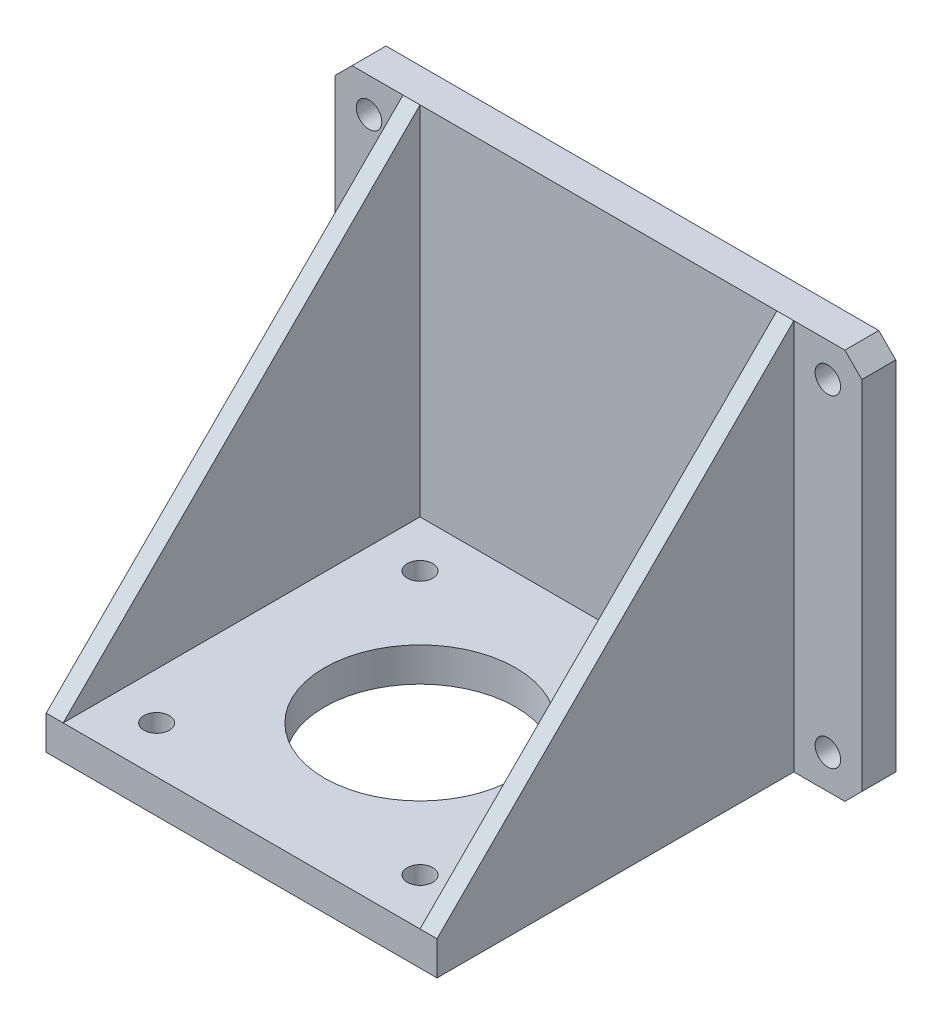
SolidWorks part; units mm, degrees
ref_plane "Front" through (0, 0, 0) normal (0, 0, 1) x (1, 0, 0)
ref_plane "Top" through (0, 0, 0) normal (0, 1, 0) x (1, 0, 0)
ref_plane "Right" through (0, 0, 0) normal (1, 0, 0) x (0, 0, -1)
sketch "Sketch1" plane through (0, 0, 0) normal (0, 1, 0) x (1, 0, 0)
  line L1 (0, 0) -> (46, 0)
  line L2 (0, 0) -> (0, 46)
  line L3 (0, 46) -> (46, 46)
  line L4 (46, 0) -> (46, 46)
  dimension "D1" = 46
  dimension "D2" = 46
extrude "Boss-Extrude1" add sketch "Sketch1" along normal blind 4
sketch "Sketch2" plane through (0, 4, 0) normal (0, 1, 0) x (1, 0, 0)
  line L0 (46, 0) -> (46, 46) construction
  line L1 (0, 46) -> (46, 46)
  line L2 (0, 46) -> (0, 42)
  line L3 (0, 42) -> (46, 42)
  line L4 (46, 46) -> (46, 42)
  dimension "D1" = 4
extrude "Boss-Extrude2" add sketch "Sketch2" along normal blind 42
sketch "Sketch3" plane through (0, 4, 0) normal (0, 1, 0) x (1, 0, 0)
  line L0 (0, 42) -> (46, 42) construction
  line L1 (0, 0) -> (2, 0)
  line L2 (0, 0) -> (0, 42)
  line L3 (0, 42) -> (2, 42)
  line L4 (2, 0) -> (2, 42)
  line L6 (44, 42) -> (46, 42)
  line L7 (44, 42) -> (44, 0)
  line L8 (44, 0) -> (46, 0)
  line L9 (46, 42) -> (46, 0)
  dimension "D1" = 2
  dimension "D2" = 2
extrude "Boss-Extrude3" add sketch "Sketch3" along normal blind 42
chamfer "Chamfer1" distance 42 angle 45 2 edges at (45, 46, 0) (1, 46, 0)
sketch "Sketch4" plane through (0, 4, 0) normal (0, 1, 0) x (1, 0, 0)
  line L0 (2, 0) -> (44, 0) construction
  line L1 (2, 0) -> (2, 42) construction
  line L2 (23, 0) -> (23, 42) construction
  line L3 (2, 42) -> (44, 42) construction
  line L4 (23, 42) -> (2, 21) construction
  line L5 (2, 42) -> (2, 0) construction
  line L6 (2, 21) -> (40, 21) construction
  circle A0 centre (23, 21) radius 11.25
  dimension "D1" = 22.5
extrude "Cut-Extrude1" cut sketch "Sketch4" against normal blind 42
sketch "Sketch5" plane through (0, 4, 0) normal (0, 1, 0) x (1, 0, 0)
  line L0 (0, 0) -> (0, 42) construction
  line L1 (2, 42) -> (44, 42) construction
  line L2 (46, 42) -> (46, 0) construction
  line L3 (2, 0) -> (44, 0) construction
  circle A0 centre (7.5, 36.5) radius 1.5
  circle A1 centre (7.5, 5.5) radius 1.5
  circle A2 centre (38.5, 5.5) radius 1.5
  circle A3 centre (38.5, 36.5) radius 1.5
  dimension "D9" = 3
  dimension "D10" = 3
  dimension "D11" = 3
  dimension "D12" = 3
  dimension "D1" = 7.5
  dimension "D2" = 5.5
  dimension "D3" = 5.5
  dimension "D4" = 7.5
  dimension "D5" = 5.5
  dimension "D6" = 7.5
  dimension "D7" = 5.5
  dimension "D8" = 7.5
extrude "Cut-Extrude2" cut sketch "Sketch5" against normal blind 42
sketch "Sketch7" plane through (0, 0, 0) normal (-1, 0, 0) x (0, 0, 1)
  line L0 (-46, 0) -> (0, 0) construction
  line L1 (-46, 46) -> (-42, 46)
  line L2 (-46, 46) -> (-46, 0)
  line L3 (-46, 0) -> (-42, 0)
  line L4 (-42, 46) -> (-42, 0)
  dimension "D1" = 4
extrude "Boss-Extrude4" add sketch "Sketch7" along normal blind 8
sketch "Sketch8" plane through (46, 0, 0) normal (1, 0, 0) x (0, 0, -1)
  line L0 (0, 0) -> (46, 0) construction
  line L1 (46, 46) -> (42, 46)
  line L2 (46, 46) -> (46, 0)
  line L3 (46, 0) -> (42, 0)
  line L4 (42, 46) -> (42, 0)
  dimension "D1" = 4
extrude "Boss-Extrude5" add sketch "Sketch8" along normal blind 8
chamfer "Chamfer2" distance 2 angle 45 4 edges at (54, 0, -44) (54, 46, -44) (-8, 0, -44) (-8, 46, -44)
sketch "Sketch6" plane through (0, 0, -42) normal (0, 0, 1) x (1, 0, 0)
  line L4 (-8, 2) -> (-8, 44) construction
  line L5 (-6, 46) -> (0, 46) construction
  line L6 (-6, 0) -> (0, 0) construction
  line L7 (52, 46) -> (46, 46) construction
  line L8 (54, 44) -> (54, 2) construction
  line L9 (52, 0) -> (46, 0) construction
  circle A0 centre (-4, 42) radius 1.5
  circle A1 centre (-4, 4) radius 1.5
  circle A2 centre (50, 4) radius 1.5
  circle A3 centre (50, 42) radius 1.5
  point P10 (-3.804, 40.5)
  point P11 (50.2686, 40.5)
  point P12 (50.2686, 9.5)
  point P13 (-3.804, 9.5)
  dimension "D9" = 3
  dimension "D10" = 3
  dimension "D11" = 3
  dimension "D12" = 3
  dimension "D2" = 4
  dimension "D3" = 4
  dimension "D4" = 4
  dimension "D5" = 4
  dimension "D6" = 4
  dimension "D7" = 4
  dimension "D8" = 4
  dimension "D13" = 4
extrude "Cut-Extrude3" cut sketch "Sketch6" against normal blind 42
